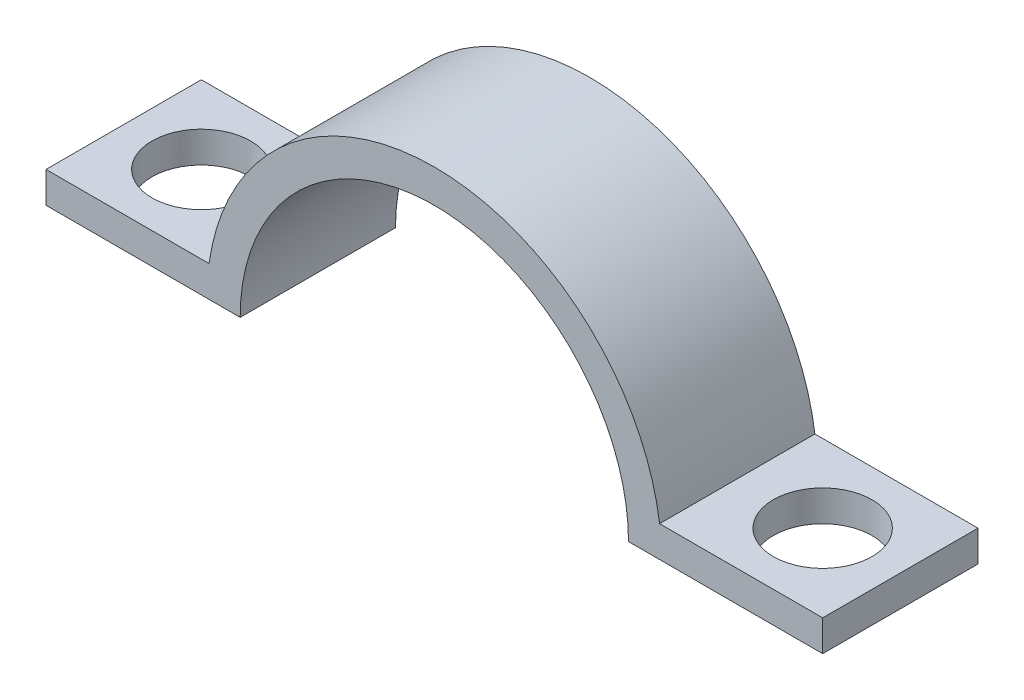
SolidWorks part; units mm, degrees
ref_plane "Front Plane" through (0, 0, 0) normal (0, 0, 1) x (1, 0, 0)
ref_plane "Top Plane" through (0, 0, 0) normal (0, 1, 0) x (1, 0, 0)
ref_plane "Right Plane" through (0, 0, 0) normal (1, 0, 0) x (0, 0, -1)
sketch "Sketch1" plane through (0, 0, 0) normal (0, 0, 1) x (1, 0, 0)
  line L1 (133.2541, 0) -> (133.2541, 8)
  line L3 (133.2541, 8) -> (91.2541, 8)
  line L4 (-66.7459, 0) -> (-66.7459, 8)
  line L5 (-66.7459, 8) -> (-24.7459, 8)
  line L7 (-66.7459, 0) -> (-16.7459, 0)
  line L9 (83.2541, 0) -> (133.2541, 0)
  arc A4 (91.2541, 8) -> (-24.7459, 8) centre (33.2541, 0) ccw
  arc A6 (83.2541, 0) -> (-16.7459, 0) centre (33.2541, 0) ccw
extrude "Boss-Extrude1" add sketch "Sketch1" along normal blind 40
sketch "Sketch2" plane through (0, 8, 0) normal (0, 1, 0) x (1, 0, 0)
  circle A0 centre (-46.7459, -20) radius 12.7
  circle A1 centre (113.2541, -20) radius 12.7
extrude "Cut-Extrude2" cut sketch "Sketch2" against normal blind 40
